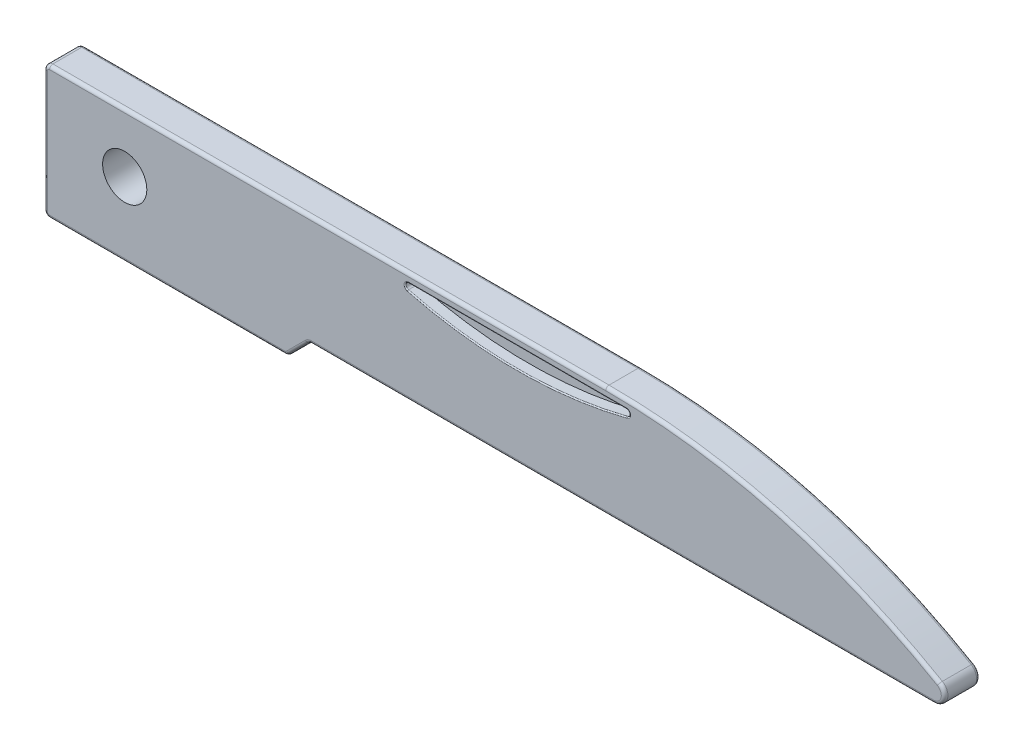
SolidWorks part; units mm, degrees
ref_plane "Płaszczyzna przednia" through (0, 0, 0) normal (0, 0, 1) x (1, 0, 0)
ref_plane "Płaszczyzna górna" through (0, 0, 0) normal (0, 1, 0) x (1, 0, 0)
ref_plane "Płaszczyzna prawa" through (0, 0, 0) normal (1, 0, 0) x (0, 0, -1)
sketch "Sketch1" plane through (0, 0, 0) normal (0, 0, 1) x (1, 0, 0)
  line L0 (4.4636, 0) -> (-6.5364, 0)
  line L1 (-6.5364, 0) -> (-6.5364, 6)
  line L2 (-6.5364, 6) -> (18.8805, 6)
  line L3 (4.4636, 0) -> (5.4636, 1)
  line L4 (5.4636, 1) -> (35.4636, 1)
  arc A1 (18.8805, 6) -> (35.4636, 1) centre (18.8805, -24) cw
  dimension "D5" = 30
  dimension "D1" = 6
  dimension "D2" = 30
  dimension "D3" = 42
  dimension "D4" = 5
  dimension "D6" = 135
extrude "Boss-Extrude1" add sketch "Sketch1" along normal blind 1.6
fillet "Fillet1" radius 0.5 1 edges at (35.4636, 1, 0.8)
fillet "Fillet2" radius 0.25 4 edges at (5.4636, 1, 0.8) (4.4636, 0, 0.8) (-6.5364, 0, 0.8) (-6.5364, 6, 0.8)
fillet "Fillet3" radius 0.15 22 edges at (-6.4632, 0.0732, 0) (-6.5364, 3, 0) (-6.4632, 5.9268, 0) (6.2971, 6, 0) (26.6918, 4.9652, 0) (34.1957, 1.3698, 0) (19.64, 1, 0) (5.4715, 0.981, 0) (4.9636, 0.5, 0) (4.4557, 0.019, 0) (26.6918, 4.9652, 1.6) (34.1957, 1.3698, 1.6) (19.64, 1, 1.6) (5.4715, 0.981, 1.6) (4.9636, 0.5, 1.6) (4.4557, 0.019, 1.6) (-0.9632, 0, 1.6) (-6.4632, 0.0732, 1.6) (-6.5364, 3, 1.6) (-6.4632, 5.9268, 1.6) (-0.9632, 0, 0) (6.2971, 6, 1.6)
sketch "Sketch2" plane through (0, 0, 0) normal (0, 0, 1) x (1, 0, 0)
  line L0 (-6.3864, 5.75) -> (-6.3864, 0.25) construction
  line L2 (-6.2864, 0.15) -> (4.3601, 0.15) construction
  circle A0 centre (-2.8864, 3.35) radius 1
  point P2 (0, 0)
  dimension "D1" = 2
  dimension "D2" = 3.5
  dimension "D3" = 3.2
extrude "Cut-Extrude3" cut sketch "Sketch2" along normal through all
sketch "Sketch3" plane through (0, 0, 1.6) normal (0, 0, 1) x (1, 0, 0)
  line L0 (20.8805, 5.6) -> (8.8805, 5.6)
  line L1 (18.8805, 5.85) -> (-6.2864, 5.85) construction
  arc A0 (8.8805, 5.6) -> (20.8805, 5.6) centre (14.8805, 24.6788) ccw
  point P5 (0, 0)
  dimension "D2" = 20
  dimension "D1" = 12
  dimension "D3" = 0.25
  dimension "D4" = 10
extrude "Cut-Extrude4" cut sketch "Sketch3" against normal blind 0.5
fillet "Fillet4" radius 0.15 2 edges at (20.8805, 5.6, 1.35) (8.8805, 5.6, 1.35)
fillet "Fillet5" radius 0.05 4 edges at (19.9564, 5.4688, 1.6) (14.8805, 4.6788, 1.6) (9.8046, 5.4688, 1.6) (14.8805, 5.6, 1.6)
